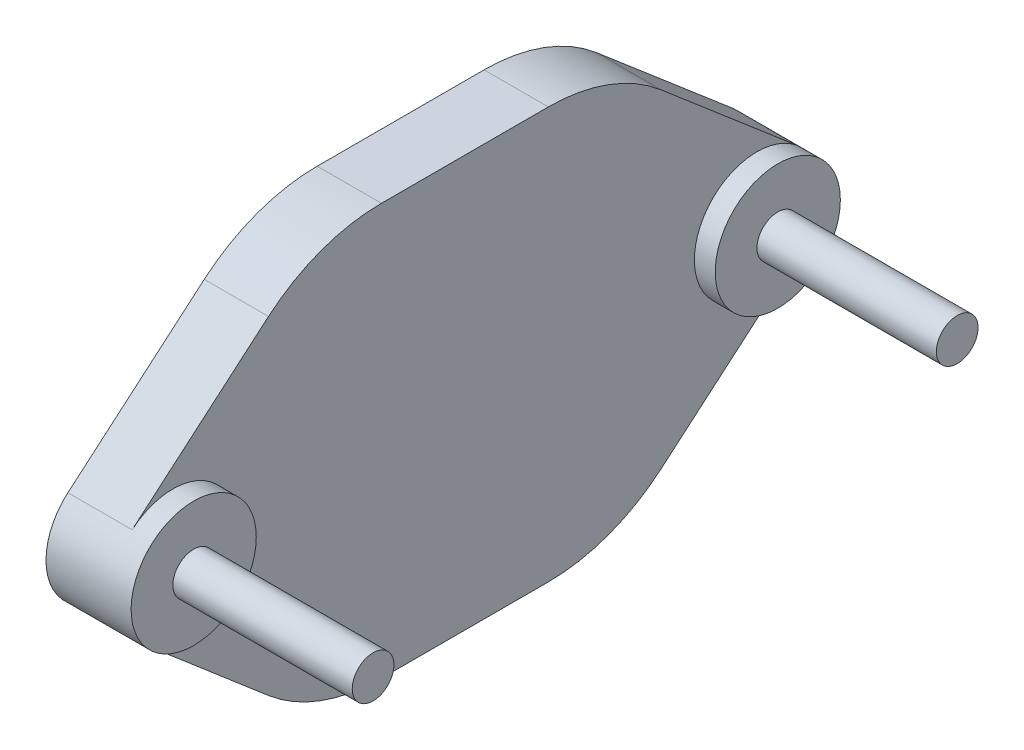
SolidWorks part; units mm, degrees
ref_plane "Front Plane" through (0, 0, 0) normal (0, 0, 1) x (1, 0, 0)
ref_plane "Top Plane" through (0, 0, 0) normal (0, 1, 0) x (1, 0, 0)
ref_plane "Right Plane" through (0, 0, 0) normal (1, 0, 0) x (0, 0, -1)
sketch "Sketch1" plane through (0, 0, 0) normal (1, 0, 0) x (0, 0, -1)
  line L0 (-25.4, 62.611) -> (25.4, 62.611)
  line L1 (-107.95, -62.611) -> (107.95, -62.611) construction
  line L2 (-107.95, -62.611) -> (-107.95, 62.611) construction
  line L3 (-107.95, 62.611) -> (107.95, 62.611) construction
  line L4 (107.95, -62.611) -> (107.95, 62.611) construction
  line L5 (-107.95, -62.611) -> (107.95, 62.611) construction
  line L6 (-107.95, 62.611) -> (107.95, -62.611) construction
  line L7 (-101.281, 14.478) -> (-59.7774, 49.9703)
  line L8 (-101.281, -14.478) -> (-59.7774, -49.9703)
  line L9 (-25.4, -62.611) -> (25.4, -62.611)
  line L10 (101.2694, 14.4879) -> (59.7372, 49.9468)
  line L11 (101.2694, -14.488) -> (59.7372, -49.9468)
  circle A0 centre (88.9, 0) radius 19.05
  circle A1 centre (-88.9, 0) radius 19.05
  arc A2 (-25.4, 62.611) -> (-59.7774, 49.9703) centre (-25.4, 9.5445) ccw
  arc A3 (-25.4, -62.611) -> (-59.7774, -49.9703) centre (-25.4, -9.5445) cw
  arc A4 (25.4, 62.611) -> (59.7372, 49.9468) centre (25.4, 9.7285) cw
  arc A5 (25.4, -62.611) -> (59.7372, -49.9468) centre (25.4, -9.7285) ccw
  point P0 (0, 0)
  point P13 (0, 62.611)
  point P21 (0, -62.611)
  dimension "D3" = 38.1
  dimension "D1" = 125.222
  dimension "D2" = 215.9
  dimension "D4" = 50.8
  dimension "D5" = 14.478
  dimension "D6" = 54.61
  dimension "D7" = 88.9
  dimension "D8" = 88.9
  dimension "D9" = 14.478
  dimension "D10" = 54.61
extrude "Boss-Extrude1" add sketch "Sketch1" along normal blind 19.558 contours L9 A5 L11 A0 L10 A4 L0 A2 L7 A1 L8 A3 | A0 | A1
sketch "Sketch2" plane through (19.558, 0, 0) normal (1, 0, 0) x (0, 0, -1)
  circle A0 centre (-88.9, 0) radius 6.35
  circle A1 centre (88.9, 0) radius 6.35
  dimension "D1" = 12.7
  dimension "D2" = 12.7
extrude "Boss-Extrude2" add sketch "Sketch2" along normal blind 60.96
sketch "Sketch3" plane through (19.558, 0, 0) normal (1, 0, 0) x (0, 0, -1)
  circle A0 centre (-88.9, 0) radius 19.05
  circle A1 centre (88.9, 0) radius 19.05
extrude "Boss-Extrude3" add sketch "Sketch3" along normal blind 6.35
